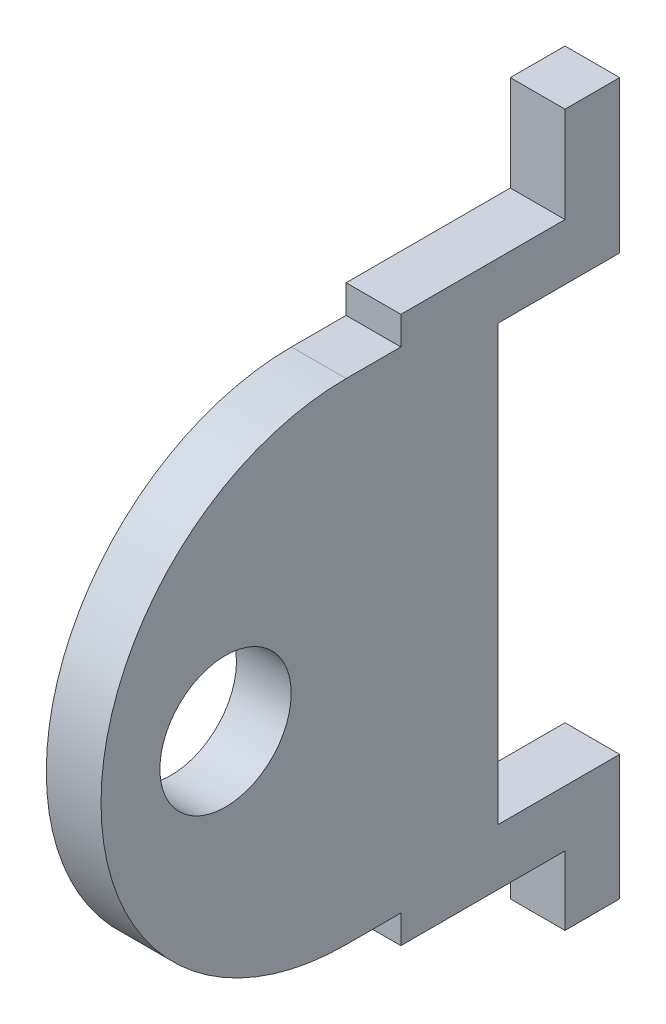
SolidWorks part; units mm, degrees
material "6061-T6 (SS)"
ref_plane "Front Plane" through (0, 0, 0) normal (1, 0, 0) x (0, 1, 0)
ref_plane "Top Plane" through (0, 0, 0) normal (0, 0, 1) x (0, 1, 0)
ref_plane "Right Plane" through (0, 0, 0) normal (0, 1, 0) x (-1, 0, 0)
sketch "Sketch3" plane through (0, 0, 0) normal (1, 0, 0) x (0, 1, 0)
  line L16 (-19.8628, 0) -> (-19.8628, 3.175)
  line L17 (-19.8628, 3.175) -> (-15.8648, 3.175)
  line L18 (-15.8648, 3.175) -> (-15.8648, 12.7)
  line L19 (-15.8648, 12.7) -> (15.8648, 12.7)
  line L20 (15.8648, 12.7) -> (15.8648, 3.175)
  line L21 (15.8648, 3.175) -> (21.4122, 3.175)
  line L22 (21.4122, 3.175) -> (21.4122, 0)
  line L24 (-19.8628, 0) -> (-12.5984, 0)
  line L25 (-12.5984, 0) -> (-12.5984, 7.0612)
  line L26 (-12.5984, 7.0612) -> (12.5984, 7.0612)
  line L27 (12.5984, 7.0612) -> (12.5984, 0)
  line L28 (12.5984, 0) -> (21.4122, 0)
  point P2 (0, 7.0612)
  point P14 (0, 12.7)
  dimension "D1" = 12.7
  dimension "D2" = 12.7
  dimension "D3" = 3.175
  dimension "D4" = 3.175
  dimension "D5" = 41.275
  dimension "D6" = 25.1968
  dimension "D7" = 31.7297
  dimension "D8" = 5.6388
extrude "Boss-Extrude1" add sketch "Sketch3" against normal mid plane 3.175
sketch "Sketch4" plane through (0, 0, 0) normal (1, 0, 0) x (0, 1, 0)
  line L0 (-14.224, 12.7) -> (-14.224, 15.875)
  line L1 (15.8648, 12.7) -> (-15.8648, 12.7) construction
  line L2 (14.224, 15.875) -> (14.224, 12.7)
  line L3 (15.8648, 12.7) -> (14.224, 12.7)
  line L15 (-19.8628, 0) -> (-12.5984, 0)
  line L16 (-12.5984, 0) -> (-12.5984, 7.0612)
  line L17 (-12.5984, 7.0612) -> (12.5984, 7.0612)
  line L18 (12.5984, 7.0612) -> (12.5984, 0)
  line L19 (12.5984, 0) -> (21.4122, 0)
  line L20 (21.4122, 0) -> (21.4122, 3.175)
  line L21 (21.4122, 3.175) -> (15.8648, 3.175)
  line L22 (15.8648, 3.175) -> (15.8648, 12.7)
  line L23 (15.8648, 12.7) -> (-15.8648, 12.7)
  line L24 (-15.8648, 12.7) -> (-15.8648, 3.175)
  line L25 (-15.8648, 3.175) -> (-19.8628, 3.175)
  line L26 (-19.8628, 3.175) -> (-19.8628, 0)
  line L27 (-19.8628, 0) -> (-12.5984, 0)
  line L28 (-12.5984, 0) -> (-12.5984, 7.0612)
  line L29 (-12.5984, 7.0612) -> (12.5984, 7.0612)
  line L30 (12.5984, 7.0612) -> (12.5984, 0)
  line L31 (12.5984, 0) -> (21.4122, 0)
  line L32 (21.4122, 0) -> (21.4122, 3.175)
  line L33 (21.4122, 3.175) -> (15.8648, 3.175)
  line L34 (15.8648, 3.175) -> (15.8648, 12.7)
  line L35 (-14.224, 12.7) -> (-15.8648, 12.7)
  line L36 (-15.8648, 12.7) -> (-15.8648, 3.175)
  line L37 (-15.8648, 3.175) -> (-19.8628, 3.175)
  line L38 (-19.8628, 3.175) -> (-19.8628, 0)
  arc A0 (-14.224, 15.875) -> (14.224, 15.875) centre (0, 15.875) cw
  point P6 (0, 30.099)
  dimension "D2" = 14.224
  dimension "D1" = 3.175
  dimension "D3" = 0
extrude "Boss-Extrude2" add sketch "Sketch4" along normal mid plane 3.175
sketch "Sketch5" plane through (1.5875, 0, 0) normal (1, 0, 0) x (0, 1, 0)
  circle A0 centre (0, 22.8736) radius 3.81
  arc A1 (14.224, 15.875) -> (-14.224, 15.875) centre (0, 15.875) ccw construction
  point P2 (0, 0)
  dimension "D1" = 7.62
  dimension "D2" = 6.9986
extrude "Cut-Extrude1" cut sketch "Sketch5" against normal blind 3.175
equation "\"A\"= 1.125in"
equation "\"B\"= 0.125"
equation "\"C\"= 0.5in"
equation "\"D\"= 0.125"
equation "\"E\"= 0.375"
